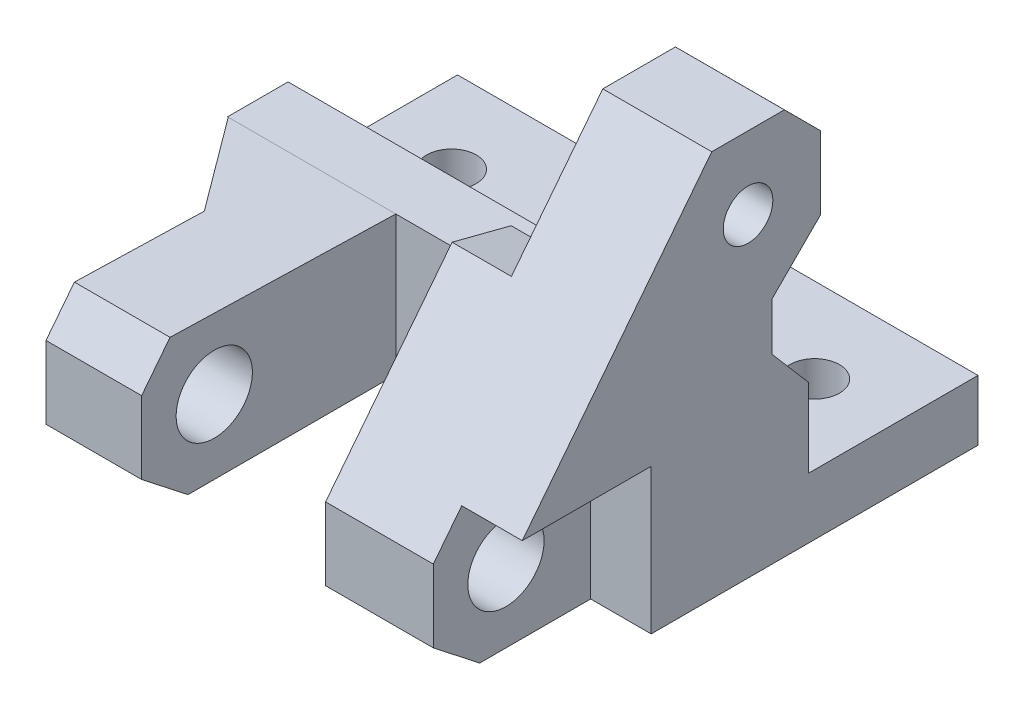
SolidWorks part; units mm, degrees
material "AISI 1020"
ref_plane "Front Plane" through (0, 0, 0) normal (0, 0, 1) x (1, 0, 0)
ref_plane "Top Plane" through (0, 0, 0) normal (0, 1, 0) x (1, 0, 0)
ref_plane "Right Plane" through (0, 0, 0) normal (1, 0, 0) x (0, 0, -1)
sketch "Sketch1" plane through (0, 0, 0) normal (1, 0, 0) x (0, 0, -1)
  line L0 (0, 0) -> (14, 0)
  line L1 (14, 0) -> (14, -5)
  line L2 (14, -5) -> (-22.1671, -5)
  line L3 (-22.1671, -5) -> (-26, -2)
  line L4 (-26, -2) -> (-26, 4)
  line L5 (-26, 4) -> (-7.9981, 27)
  line L6 (-7.9981, 27) -> (-1.9981, 27)
  line L12 (0, 6.5) -> (0, 0)
  line L13 (-1.9981, 27) -> (1.0019, 24.0037)
  line L14 (1.0019, 24.0037) -> (1.0019, 18.0037)
  line L15 (1.0019, 18.0037) -> (-3.0003, 14)
  line L16 (-3.0003, 14) -> (-3.0003, 10)
  line L17 (-3.0003, 10) -> (0, 6.5)
  circle A0 centre (-20, 1.1042) radius 3.15
  circle A1 centre (-5, 21) radius 2.05
  point P16 (0, 0)
  point P17 (0, 0)
  point P18 (-19.7835, 0.5996)
  point P19 (-5.9896, 21.2609)
  point P20 (-19.8657, 1.2576)
  point P21 (-19.1584, -5)
  point P24 (0, 0)
  point P25 (0, 0)
  dimension "D16" = 6.1042
  dimension "D1" = 5
  dimension "D2" = 14
  dimension "D3" = 32
  dimension "D4" = 51.95
  dimension "D5" = 6.5
  dimension "D6" = 3
  dimension "D7" = 6
  dimension "D8" = 40
  dimension "D9" = 6
  dimension "D10" = 4.24
  dimension "D11" = 3
  dimension "D12" = 4
  dimension "D13" = 3.5
  dimension "D14" = 4.61
  dimension "D15" = 6
  dimension "D17" = 26
  dimension "D18" = 15
  dimension "D19" = 34
extrude "Boss-Extrude1" add sketch "Sketch1" against normal blind 13.9
sketch "Sketch2" plane through (0, 0, 0) normal (1, 0, 0) x (0, 0, -1)
  line L0 (-23.6519, 7) -> (-13, 7)
  line L1 (-26, 4) -> (-7.9981, 27) construction
  line L2 (-13, 7) -> (-13, -5)
  line L3 (14, -5) -> (-22.1671, -5) construction
  line L4 (-26, -2) -> (-26, 4) construction
  line L5 (-23.6519, 7) -> (-26, 4)
  line L6 (-26, 4) -> (-26, -2)
  line L7 (-26, -2) -> (-22.1671, -5)
  line L8 (-22.1671, -5) -> (-13, -5)
  dimension "D1" = 12
  dimension "D2" = 13
extrude "Cut-Extrude1" cut sketch "Sketch2" against normal blind 5
sketch "Sketch4" plane through (-13.9, 0, 0) normal (-1, 0, 0) x (0, 0, 1)
  line L0 (7.9981, 27) -> (23.6519, 7) construction
  line L1 (3.0003, 14) -> (9.0003, 14)
  line L2 (15.5484, 17.3535) -> (10.6684, 16.0936)
  line L3 (10.6684, 16.0936) -> (9.0003, 14)
  line L4 (15.5484, 17.3535) -> (7.9981, 27)
  line L5 (7.9981, 27) -> (1.9981, 27)
  line L6 (1.9981, 27) -> (-1.0019, 24.0037)
  line L7 (-1.0019, 24.0037) -> (-1.0019, 18.0037)
  line L8 (-1.0019, 18.0037) -> (3.0003, 14)
  point P0 (15.5484, 17.3535)
  dimension "D1" = 12.25
  dimension "D2" = 5.04
  dimension "D3" = 4.88
extrude "Cut-Extrude2" cut sketch "Sketch4" against normal blind 4.9
sketch "Sketch5" plane through (-13.9, 0, 0) normal (-1, 0, 0) x (0, 0, 1)
  line L0 (0, 0) -> (-14, 0)
  line L1 (-14, 0) -> (-14, -5)
  line L2 (-14, -5) -> (-14, 0) construction
  line L3 (-14, -5) -> (5, -5)
  line L4 (22.1671, -5) -> (-14, -5) construction
  line L5 (5, -5) -> (5, 6.5)
  line L6 (5, 6.5) -> (0, 6.5)
  line L7 (0, 0) -> (0, 6.5) construction
  line L8 (0, 6.5) -> (0, 0)
  dimension "D1" = 19
  dimension "D2" = 11.5
extrude "Boss-Extrude2" add sketch "Sketch5" along normal blind 29.1
sketch "Sketch6" plane through (-13.9, 0, 0) normal (-1, 0, 0) x (0, 0, 1)
  line L0 (5, -5) -> (22.1671, -5)
  line L1 (22.1671, -5) -> (26, -2)
  line L2 (26, -2) -> (26, 4)
  line L3 (26, 4) -> (23.6519, 7)
  line L4 (15.5484, 17.3535) -> (26, 4) construction
  line L5 (5, 6.5) -> (23.6519, 7)
  circle A0 centre (20, 1.1042) radius 3.15
  circle M4 centre (20, 1.1042) radius 3.15
  line M6 (5, 6.5) -> (5, -5)
  line M7 (5, -5) -> (22.1671, -5)
  line M8 (22.1671, -5) -> (26, -2)
  line M9 (26, -2) -> (26, 4)
  line M10 (26, 4) -> (15.5484, 17.3535)
  dimension "D1" = 12
extrude "Boss-Extrude3" add sketch "Sketch6" along normal blind 7.9 from offset 15.2 contours L5 M6 M7 M8 M9 M10 M4
sketch "Sketch7" plane through (-37, 0, 0) normal (-1, 0, 0) x (0, 0, 1)
  line L0 (5, 6.5) -> (23.6519, 7)
  line L1 (23.6519, 7) -> (26, 4)
  line L2 (26, 4) -> (26, -2)
  line L3 (26, -2) -> (22.1671, -5)
  line L4 (22.1671, -5) -> (5, -5)
  line L5 (5, -5) -> (5, 6.5)
extrude "Boss-Extrude4" add sketch "Sketch7" along normal blind 6
sketch "Sketch8" plane through (0, 6.3614, -0.1705) normal (0, 0.9996, -0.0268) x (1, 0, 0)
  line L0 (-37, -26.0979) -> (-37, -13.0979)
  line L1 (-43, -26.0979) -> (-29.1, -26.0979) construction
  line L2 (-37, -13.0979) -> (-43, -5.0979)
  line L3 (-43, -23.831) -> (-43, -5.1724) construction
  line L4 (-43, -5.0979) -> (-43, -26.0979)
  line L5 (-43, -26.0979) -> (-37, -26.0979)
  dimension "D1" = 6
  dimension "D2" = 21
  dimension "D3" = 13
extrude "Cut-Extrude3" cut sketch "Sketch8" against normal blind 23
sketch "Sketch9" plane through (0, 0, 0) normal (0, 1, 0) x (1, 0, 0)
  line L0 (-21.5, 7) -> (-21.5, 1.3395) construction
  line L1 (-43, 14) -> (0, 14) construction
  circle A0 centre (-21.5, 7) radius 2.05
  circle A1 centre (-6.5, 7) radius 2.05
  circle A2 centre (-36.5, 7) radius 2.05
  point P5 (0, 0)
  point P9 (0, 0)
  dimension "D1" = 30
  dimension "D2" = 21.5
  dimension "D3" = 7
  dimension "D4" = 7
extrude "Cut-Extrude4" cut sketch "Sketch9" against normal blind 23
equation "\"A\"= 100"
equation "\"B\"= 100"
equation "\"C\"= 100"
equation "\"D\"= 100"
equation "\"E\"= 100"
